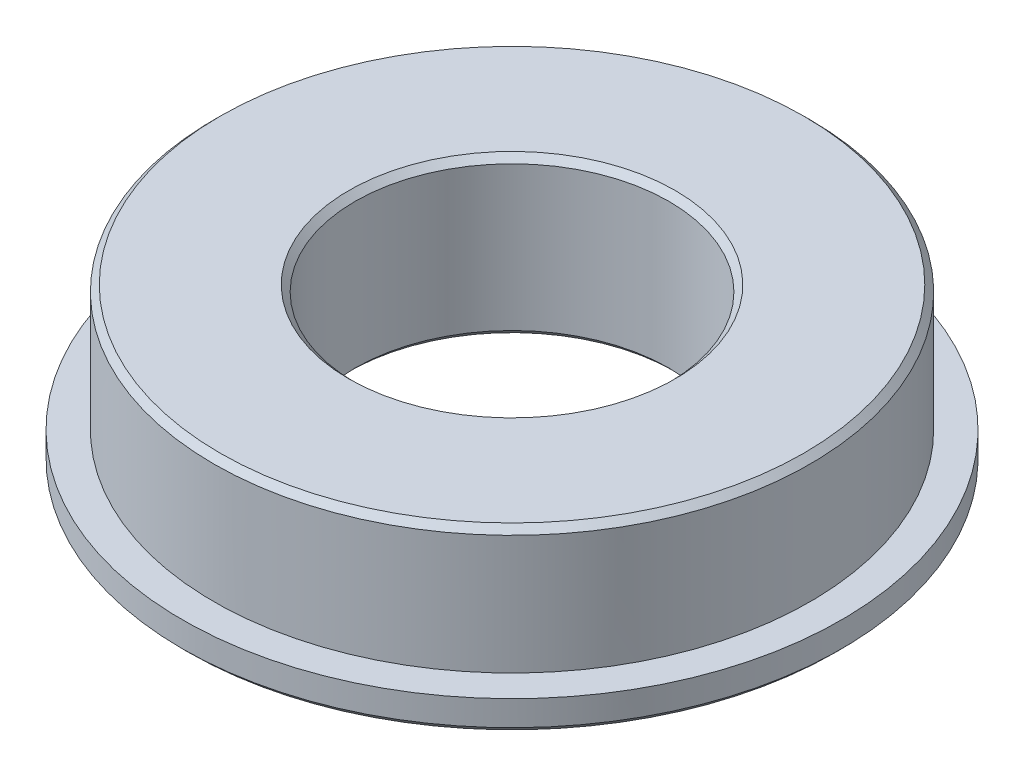
SolidWorks part; units mm, degrees
material "1023 碳钢板 (SS)"
ref_plane "前视基准面" through (0, 0, 0) normal (0, 0, 1) x (1, 0, 0)
ref_plane "上视基准面" through (0, 0, 0) normal (0, 1, 0) x (1, 0, 0)
ref_plane "右视基准面" through (0, 0, 0) normal (1, 0, 0) x (0, 0, -1)
sketch "草图1" plane through (0, 0, 0) normal (0, 1, 0) x (1, 0, 0)
  circle A0 centre (0, 0) radius 5
  circle A1 centre (0, 0) radius 9.5
  dimension "D1" = 19
  dimension "D2" = 10
extrude "凸台-拉伸1" add sketch "草图1" along normal blind 5
sketch "草图2" plane through (0, 0, 0) normal (0, -1, 0) x (1, 0, 0)
  circle A0 centre (0, 0) radius 9.5
  circle A1 centre (0, 0) radius 10.5
  dimension "D1" = 19
  dimension "D2" = 21
extrude "凸台-拉伸2" add sketch "草图2" against normal blind 1
chamfer "倒角1" distance 0.2 angle 45 4 edges at (0, 0, -10.5) (0, 5, 5) (0, 0, 5) (0, 5, 9.5)
